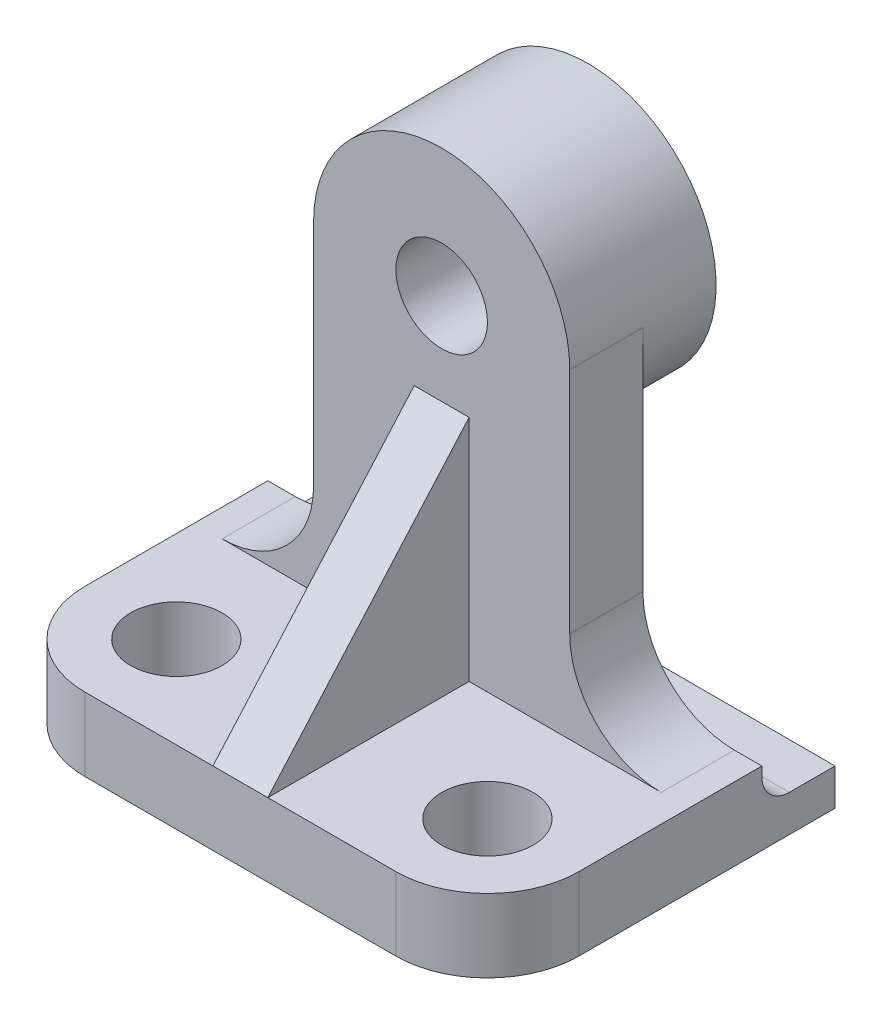
SolidWorks part; units mm, degrees
ref_plane "Ön Düzlem" through (0, 0, 0) normal (0, 0, 1) x (1, 0, 0)
ref_plane "Üst Düzlem" through (0, 0, 0) normal (0, 1, 0) x (1, 0, 0)
ref_plane "Sağ Düzlem" through (0, 0, 0) normal (1, 0, 0) x (0, 0, -1)
sketch "Sketch1" plane through (0, 0, 0) normal (1, 0, 0) x (0, 0, -1)
  line L0 (30, 8) -> (30, 7)
  line L1 (0, 0) -> (38, 0)
  line L2 (0, 0) -> (0, 8)
  line L3 (0, 8) -> (30, 8)
  line L4 (38, 0) -> (38, 4)
  line L5 (33, 4) -> (38, 4)
  arc A0 (30, 7) -> (33, 4) centre (33, 7) ccw
  point P10 (30, 4)
  dimension "D5" = 3
  dimension "D2" = 38
  dimension "D3" = 4
  dimension "D4" = 8
extrude "Boss-Extrude1" add sketch "Sketch1" against normal blind 54
fillet "Fillet1" radius 10 2 edges at (-54, 4, 0) (0, 4, 0)
sketch "Sketch2" plane through (0, 8, 0) normal (0, 1, 0) x (1, 0, 0)
  circle A0 centre (-44, 10) radius 5
  circle A1 centre (-10, 10) radius 5
  dimension "D1" = 10
extrude "Cut-Extrude1" cut sketch "Sketch2" against normal through all
sketch "Sketch3" plane through (0, 0, -30) normal (0, 0, -1) x (-1, 0, 0)
  line L0 (27, 8) -> (27, 43) construction
  line L1 (54, 8) -> (0, 8) construction
  line L2 (54, 0) -> (0, 0) construction
  line L3 (13, 43) -> (13, 8)
  line L4 (41, 43) -> (41, 8)
  line L5 (41, 8) -> (13, 8)
  circle A0 centre (27, 43) radius 14
  dimension "D2" = 28
  dimension "D1" = 43
extrude "Boss-Extrude2" add sketch "Sketch3" against normal blind 8
fillet "Fillet2" radius 10 2 edges at (-41, 8, -26) (-13, 8, -26)
sketch "Sketch4" plane through (0, 0, -30) normal (0, 0, -1) x (-1, 0, 0)
  circle A0 centre (27, 43) radius 14
extrude "Boss-Extrude3" add sketch "Sketch4" along normal blind 8
sketch "Sketch5" plane through (0, 0, -38) normal (0, 0, -1) x (-1, 0, 0)
  circle A0 centre (27, 43) radius 5
  dimension "D1" = 10
extrude "Cut-Extrude2" cut sketch "Sketch5" against normal through all
ref_plane "Plane1" through (-27, 0, 0) normal (1, 0, 0) x (0, 0, -1)
sketch "Sketch6" plane through (-27, 0, 0) normal (1, 0, 0) x (0, 0, -1)
  line L0 (0, 8) -> (22, 33)
  line L1 (22, 43) -> (22, 18) construction
  line L3 (22, 43) -> (30, 43) construction
  dimension "D1" = 10
rib "Rib1" sketch "Sketch6" sketch "Sketch6" thickness 6 extrusion direction parallel to sketch draft on no parameters "D1"=6
